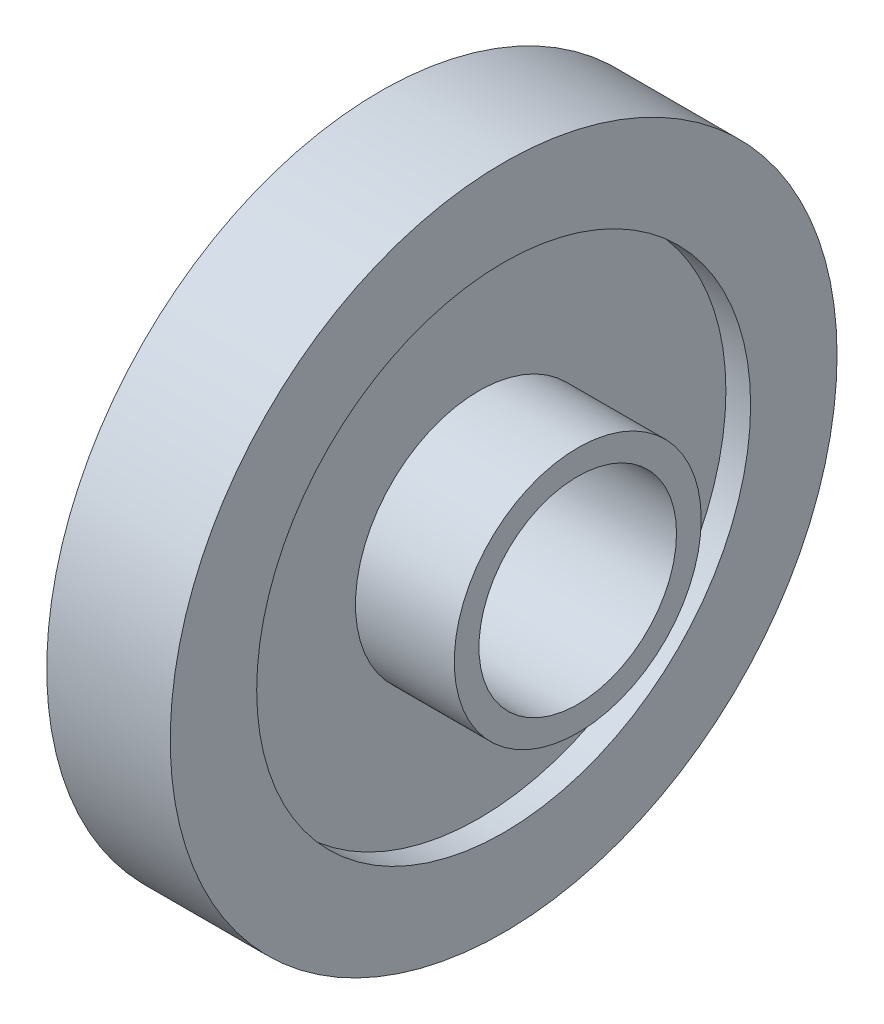
SolidWorks part; units mm, degrees
ref_plane "Alzado" through (0, 0, 0) normal (0, 0, 1) x (1, 0, 0)
ref_plane "Planta" through (0, 0, 0) normal (0, 1, 0) x (1, 0, 0)
ref_plane "Vista lateral" through (0, 0, 0) normal (1, 0, 0) x (0, 0, -1)
sketch "Croquis1" plane through (0, 0, 0) normal (1, 0, 0) x (0, 0, -1)
  circle A0 centre (0, 0) radius 13.5
  dimension "D1" = 27
extrude "Saliente-Extruir1" add sketch "Croquis1" along normal blind 5
sketch "Croquis2" plane through (5, 0, 0) normal (1, 0, 0) x (0, 0, -1)
  circle A0 centre (0, 0) radius 10
  dimension "D1" = 20
extrude "Cortar-Extruir1" cut sketch "Croquis2" against normal blind 1
sketch "Croquis3" plane through (0, 0, 0) normal (-1, 0, 0) x (0, 0, 1)
  circle A0 centre (0, 0) radius 10
  dimension "D1" = 20
extrude "Cortar-Extruir2" cut sketch "Croquis3" against normal blind 1
sketch "Croquis4" plane through (4, 0, 0) normal (1, 0, 0) x (0, 0, -1)
  circle A0 centre (0, 0) radius 5
  dimension "D2" = 10
extrude "Saliente-Extruir2" add sketch "Croquis4" along normal blind 4
sketch "Croquis5" plane through (8, 0, 0) normal (1, 0, 0) x (0, 0, -1)
  circle A0 centre (0, 0) radius 4
  dimension "D1" = 8
extrude "Cortar-Extruir4" cut sketch "Croquis5" against normal through all
